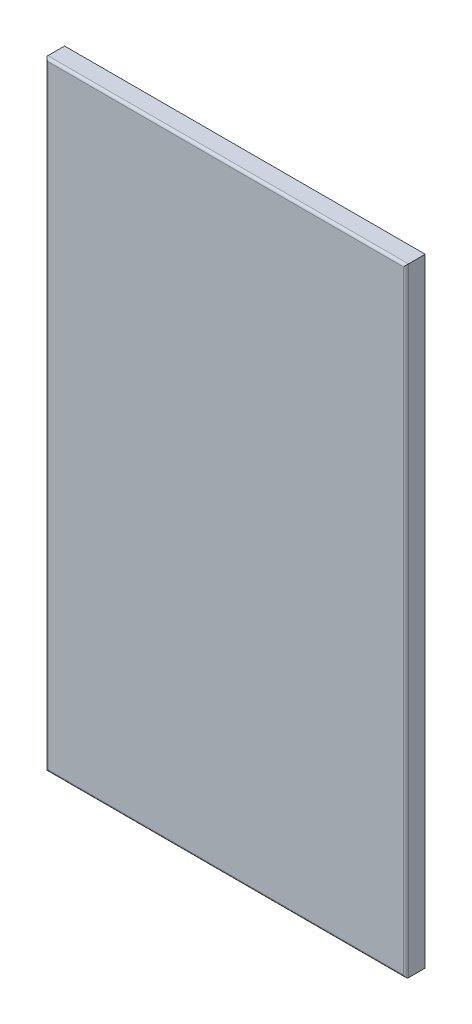
SolidWorks part; units mm, degrees
ref_plane "Front Plane" through (0, 0, 0) normal (0, 0, 1) x (1, 0, 0)
ref_plane "Top Plane" through (0, 0, 0) normal (0, 1, 0) x (1, 0, 0)
ref_plane "Right Plane" through (0, 0, 0) normal (1, 0, 0) x (0, 0, -1)
sketch "Sketch1" plane through (0, 0, 0) normal (0, 0, 1) x (1, 0, 0)
  line L1 (177.8, 304.8) -> (-177.8, 304.8)
  line L2 (177.8, 304.8) -> (177.8, -304.8)
  line L3 (177.8, -304.8) -> (-177.8, -304.8)
  line L4 (-177.8, 304.8) -> (-177.8, -304.8)
  line L5 (177.8, 304.8) -> (-177.8, -304.8) construction
  line L6 (177.8, -304.8) -> (-177.8, 304.8) construction
  point P0 (0, 0)
  dimension "D1" = 609.6
  dimension "D2" = 355.6
extrude "Boss-Extrude1" add sketch "Sketch1" along normal blind 2.54
sketch "Sketch2" plane through (0, 0, 2.54) normal (0, 0, 1) x (1, 0, 0)
  line L0 (175.26, 302.26) -> (-175.26, 302.26)
  line L1 (-175.26, 302.26) -> (-175.26, -302.26)
  line L2 (-175.26, -302.26) -> (175.26, -302.26)
  line L3 (175.26, -302.26) -> (175.26, 302.26)
  line L4 (-177.8, 304.8) -> (-177.8, -304.8)
  line L5 (-177.8, -304.8) -> (177.8, -304.8)
  line L6 (177.8, -304.8) -> (177.8, 304.8)
  line L7 (177.8, 304.8) -> (-177.8, 304.8)
  line L8 (-177.8, 304.8) -> (-177.8, -304.8)
  line L9 (-177.8, -304.8) -> (177.8, -304.8)
  line L10 (177.8, -304.8) -> (177.8, 304.8)
  line L11 (177.8, 304.8) -> (-177.8, 304.8)
  dimension "D1" = 0
  dimension "D2" = 2.54
extrude "Boss-Extrude2" add sketch "Sketch2" against normal blind 19.05
fillet "Fillet1" radius 2.54 4 edges at (0, 304.8, 2.54) (177.8, 0, 2.54) (0, -304.8, 2.54) (-177.8, 0, 2.54)
